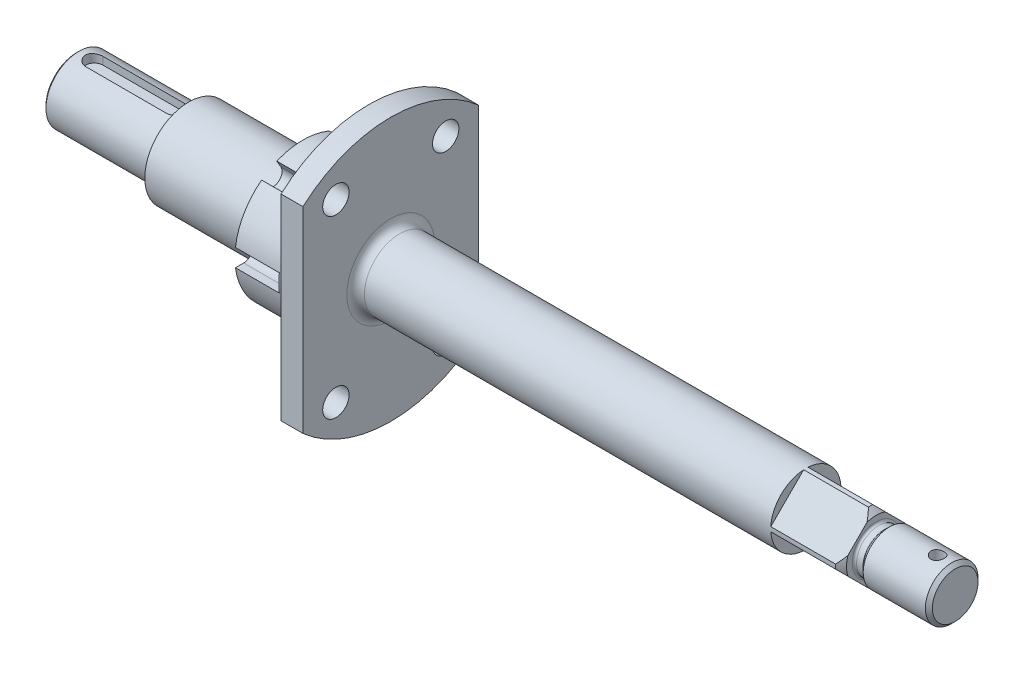
SolidWorks part; units mm, degrees
material "Сталь 20 ГОСТ 1050-2013"
ref_plane "Спереди" through (0, 0, 0) normal (0, 0, 1) x (1, 0, 0)
ref_plane "Сверху" through (0, 0, 0) normal (0, 1, 0) x (1, 0, 0)
ref_plane "Справа" through (0, 0, 0) normal (1, 0, 0) x (0, 0, -1)
sketch "Эскиз1" plane through (0, 0, 0) normal (0, 0, 1) x (1, 0, 0)
  line L0 (0, 0) -> (487.1574, 0) construction
  line L1 (129, 31) -> (103, 31)
  line L2 (103, 31) -> (103, 20)
  line L5 (0, 0) -> (0, 14)
  line L6 (1, 15) -> (51, 15)
  line L7 (51, 15) -> (51, 20)
  line L9 (51, 20) -> (103, 20)
  line L12 (133, 35) -> (133, 60)
  line L13 (133, 60) -> (143, 60)
  line L14 (143, 60) -> (143, 20)
  line L17 (147, 16) -> (361.5, 16)
  line L18 (364, 13.5) -> (364, 10.9)
  line L19 (365, 9.9) -> (367.7929, 9.9)
  line L20 (368.1464, 10.0464) -> (370.1, 12)
  line L21 (370.1, 12) -> (398.4, 12)
  line L22 (400, 10.4) -> (400, 0)
  line L23 (400, 0) -> (0, 0)
  line L25 (0, 14) -> (1, 15)
  line L26 (398.4, 12) -> (400, 10.4)
  line L27 (361.5, 16) -> (364, 13.5)
  arc A0 (143, 20) -> (147, 16) centre (147, 20) ccw
  arc A1 (129, 31) -> (133, 35) centre (129, 35) ccw
  arc A6 (367.7929, 9.9) -> (368.1464, 10.0464) centre (367.7929, 10.4) ccw
  arc A7 (364, 10.9) -> (365, 9.9) centre (365, 10.9) ccw
  point P8 (0, 15)
  point P20 (364, 16)
  point P24 (400, 12)
  point P46 (368, 9.9)
  point P49 (364, 9.9)
  dimension "D34" = 0.5
  dimension "D35" = 1
  dimension "D8" = 4
  dimension "D20" = 4
  dimension "D4" = 400
  dimension "D5" = 30
  dimension "D6" = 45
  dimension "D7" = 40
  dimension "D9" = 120
  dimension "D10" = 62
  dimension "D11" = 32
  dimension "D12" = 19.8
  dimension "D13" = 24
  dimension "D14" = 4
  dimension "D15" = 36
  dimension "D16" = 10
  dimension "D17" = 1
  dimension "D18" = 30
  dimension "D19" = 82
  dimension "D21" = 51
  dimension "D27" = 45
  dimension "D36" = 1.6
  dimension "D37" = 45
  dimension "D38" = 2.5
  dimension "D39" = 45
revolve "Повернуть1" add sketch "Эскиз1" angle 360 about L0
cosmetic thread "Условное изображение резьбы1" parameters "D2"=22.5
sketch "Эскиз2" plane through (400, 0, 0) normal (1, 0, 0) x (0, 0, -1)
  line L0 (0, -16.9706) -> (16.9706, 0)
  line L1 (0, -16.9706) -> (-16.9706, 0)
  line L2 (16.9706, 0) -> (0, 16.9706)
  line L3 (-16.9706, 0) -> (0, 16.9706)
  line L4 (0, -16.9706) -> (0, 16.9706) construction
  line L5 (16.9706, 0) -> (-16.9706, 0) construction
  point P1 (0, 0)
  dimension "D1" = 24
extrude "Вырез-Вытянуть1" cut sketch "Эскиз2" against normal blind 68 flip side to cut
ref_plane "Плоскость1" through (0, 15, 0) normal (0, 1, 0) x (1, 0, 0)
sketch "Эскиз3" plane through (0, 15, 0) normal (0, 1, 0) x (1, 0, 0)
  line L0 (8, 0) -> (45, 0) construction
  line L1 (8, 4) -> (45, 4)
  line L2 (8, -4) -> (45, -4)
  line L4 (51, 20) -> (51, -20) construction
  arc A0 (8, 4) -> (8, -4) centre (8, 0) ccw
  arc A1 (45, -4) -> (45, 4) centre (45, 0) ccw
  point P3 (26.5, 0)
  dimension "D1" = 8
  dimension "D2" = 45
  dimension "D3" = 2
extrude "Вырез-Вытянуть2" cut sketch "Эскиз3" against normal blind 4
sketch "Эскиз6" plane through (0, 0, 0) normal (0, 1, 0) x (1, 0, 0)
  line L0 (400, -10.4) -> (400, 10.4) construction
  circle A0 centre (392, 0) radius 3
  dimension "D1" = 6
  dimension "D2" = 8
extrude "Вырез-Вытянуть4" cut sketch "Эскиз6" against normal through all both and the other way through all
sketch "Эскиз7" plane through (143, 0, 0) normal (1, 0, 0) x (0, 0, -1)
  line L1 (-25, -40) -> (25, -40) construction
  line L2 (-25, -40) -> (-25, 40) construction
  line L3 (-25, 40) -> (25, 40) construction
  line L4 (25, -40) -> (25, 40) construction
  line L5 (-25, -40) -> (25, 40) construction
  line L6 (-25, 40) -> (25, -40) construction
  circle A0 centre (-25, 40) radius 6
  circle A1 centre (-25, -40) radius 6
  circle A2 centre (25, -40) radius 6
  circle A3 centre (25, 40) radius 6
  point P0 (0, 0)
  dimension "D1" = 12
  dimension "D2" = 50
  dimension "D3" = 80
extrude "Вырез-Вытянуть5" cut sketch "Эскиз7" against normal through all
sketch "Эскиз8" plane through (143, 0, 0) normal (1, 0, 0) x (0, 0, -1)
  line L1 (-40, -60) -> (40, -60)
  line L2 (-40, -60) -> (-40, 60)
  line L3 (-40, 60) -> (40, 60)
  line L4 (40, -60) -> (40, 60)
  line L5 (-40, -60) -> (40, 60) construction
  line L6 (-40, 60) -> (40, -60) construction
  circle A1 centre (0, 0) radius 60 construction
  point P0 (0, 0)
  point P7 (-40, 0)
  point P8 (40, 0)
  dimension "D1" = 80
extrude "Вырез-Вытянуть6" cut sketch "Эскиз8" against normal through all flip side to cut
sketch "Эскиз4" plane through (103, 0, 0) normal (-1, 0, 0) x (0, 0, 1)
  line L0 (0, 0) -> (35.2838, 0) construction
  line L1 (30.7409, 4) -> (27, 4)
  line L2 (27, -4) -> (30.7409, -4)
  arc A1 (30.7409, -4) -> (30.7409, 4) centre (0, 0) ccw
  arc A2 (27, 4) -> (27, -4) centre (27, 0) ccw
  circle A4 centre (0, 0) radius 31 construction
  dimension "D1" = 8
  dimension "D2" = 8
extrude "Вырез-Вытянуть3" cut sketch "Эскиз4" against normal blind 20
pattern_circular "Круговой массив1" count 6 over 360 about axis through (0, 0, 0) along (1, 0, 0) of "Вырез-Вытянуть3"
